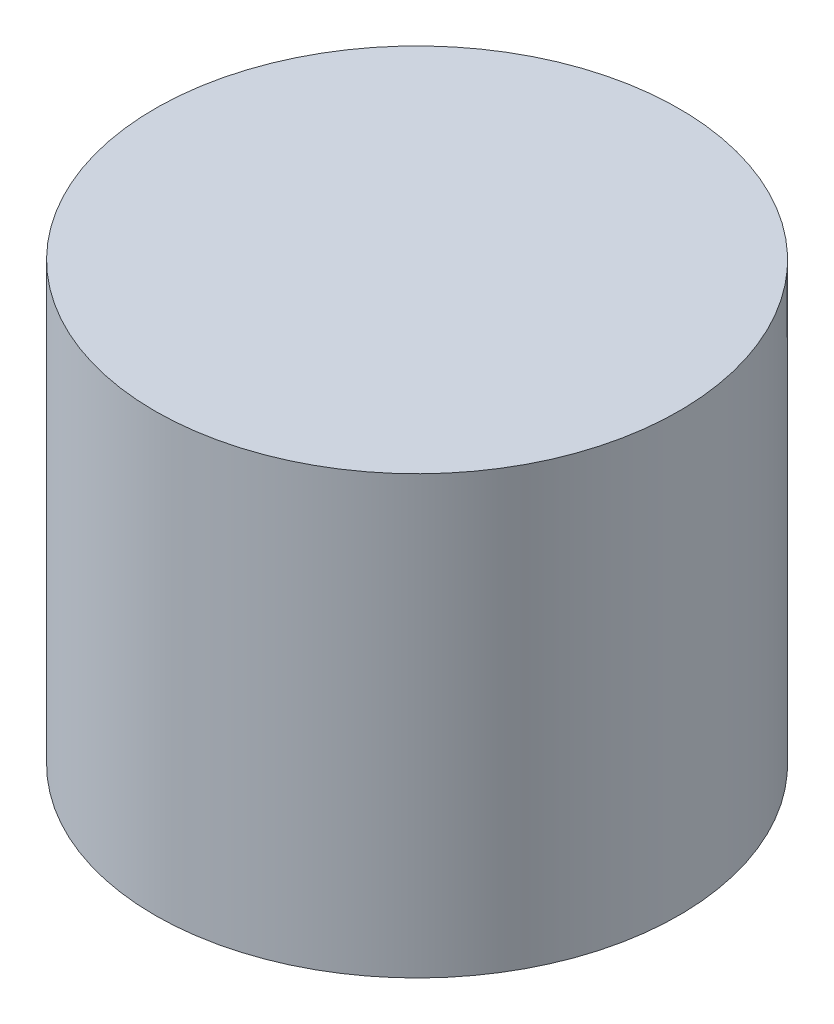
SolidWorks part; units mm, degrees
ref_plane "Front Plane" through (0, 0, 0) normal (0, 0, 1) x (1, 0, 0)
ref_plane "Top Plane" through (0, 0, 0) normal (0, 1, 0) x (1, 0, 0)
ref_plane "Right Plane" through (0, 0, 0) normal (1, 0, 0) x (0, 0, -1)
sketch "Sketch1" plane through (0, 0, 0) normal (0, 1, 0) x (1, 0, 0)
  circle A0 centre (0, 0) radius 19.05
  circle A1 centre (0, 0) radius 12.7
  dimension "D1" = 25.4
  dimension "D2" = 6.35
extrude "Boss-Extrude1" add sketch "Sketch1" along normal blind 25.4
sketch "Sketch4" plane through (0, 25.4, 0) normal (0, 1, 0) x (1, 0, 0)
  circle A0 centre (0, 0) radius 19.05
extrude "Boss-Extrude2" add sketch "Sketch4" along normal blind 6.35
sketch "Sketch5" plane through (0, 31.75, 0) normal (0, 1, 0) x (1, 0, 0)
  circle A0 centre (0, 0) radius 6.35
  dimension "D1" = 12.7
equation "\"Pstrut_L\"= 36in"
equation "\"Pstrut_D\"= 1in"
equation "\"Pstrut_T\"= 0.25"
equation "\"Sstrut_L\"= 36in"
equation "\"Sstrut_D\"= 0.5in"
equation "\"Sstrut_T\"= 0.125"
equation "\"Dstrut_L\"= 10in"
equation "\"Dstrut_D\"= 0.5in"
equation "\"Dstrut_T\"= 0.125"
equation "\"D1@Sketch1\"=\"Pstrut_D\""
equation "\"D1@Boss-Extrude2\"=\"Pstrut_T\""
